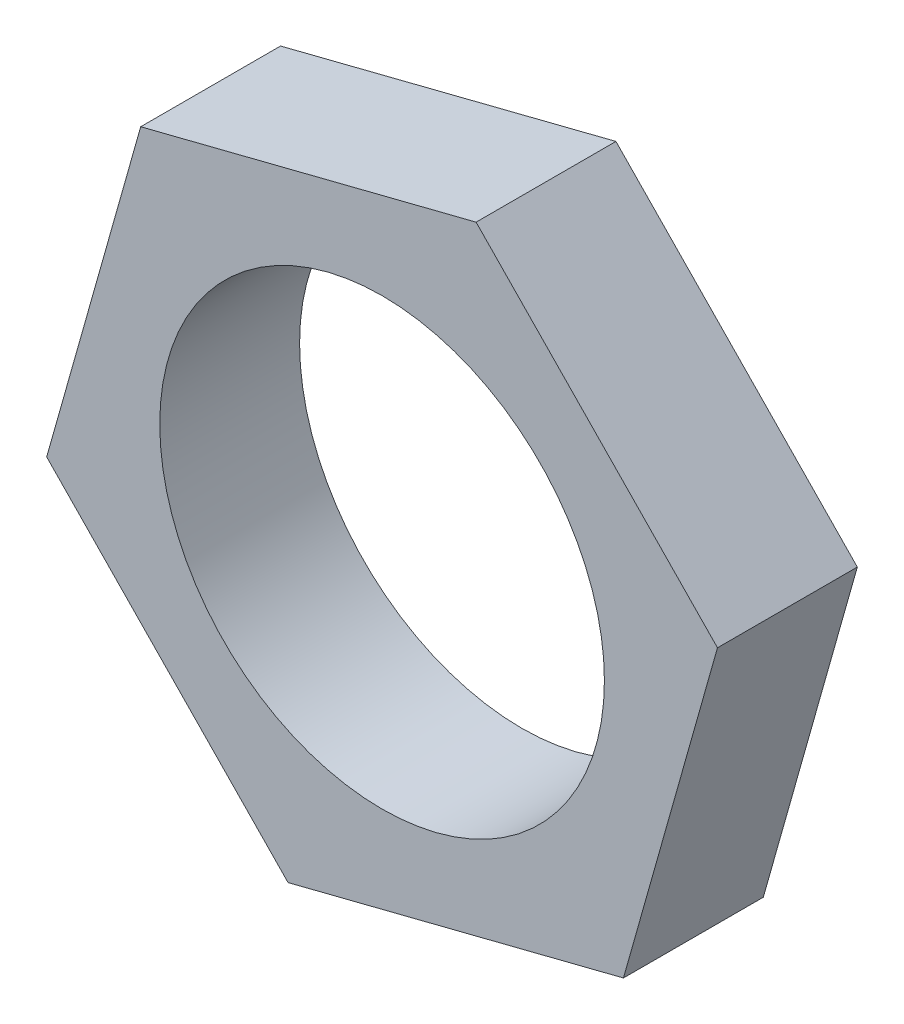
SolidWorks part; units mm, degrees
ref_plane "Front Plane" through (0, 0, 0) normal (0, 0, 1) x (1, 0, 0)
ref_plane "Top Plane" through (0, 0, 0) normal (0, 1, 0) x (1, 0, 0)
ref_plane "Right Plane" through (0, 0, 0) normal (1, 0, 0) x (0, 0, -1)
sketch "Sketch1" plane through (0, 0, 0) normal (0, 0, 1) x (1, 0, 0)
  line L1 (-1.3449, -4.7629) -> (3.4523, -3.5462)
  line L2 (3.4523, -3.5462) -> (4.7972, 1.2167)
  line L3 (4.7972, 1.2167) -> (1.3449, 4.7629)
  line L4 (1.3449, 4.7629) -> (-3.4523, 3.5462)
  line L5 (-3.4523, 3.5462) -> (-4.7972, -1.2167)
  line L6 (-4.7972, -1.2167) -> (-1.3449, -4.7629)
  circle A0 centre (0, 0) radius 4.286 construction
  circle A1 centre (0, 0) radius 3.18
  point P10 (256.1144, 156.8619)
  point P11 (177.8522, 99.815)
  point P12 (0, 0)
  point P13 (0, 168.7781)
  point P14 (0, 20.6043)
  point P15 (0, 8.8338)
  point P16 (-2.7264, 6.6243)
  point P17 (-3.4523, 3.5462)
  dimension "D1" = 6.36
extrude "Boss-Extrude1" add sketch "Sketch1" along normal blind 2
cosmetic thread "Cosmetic Thread1"
